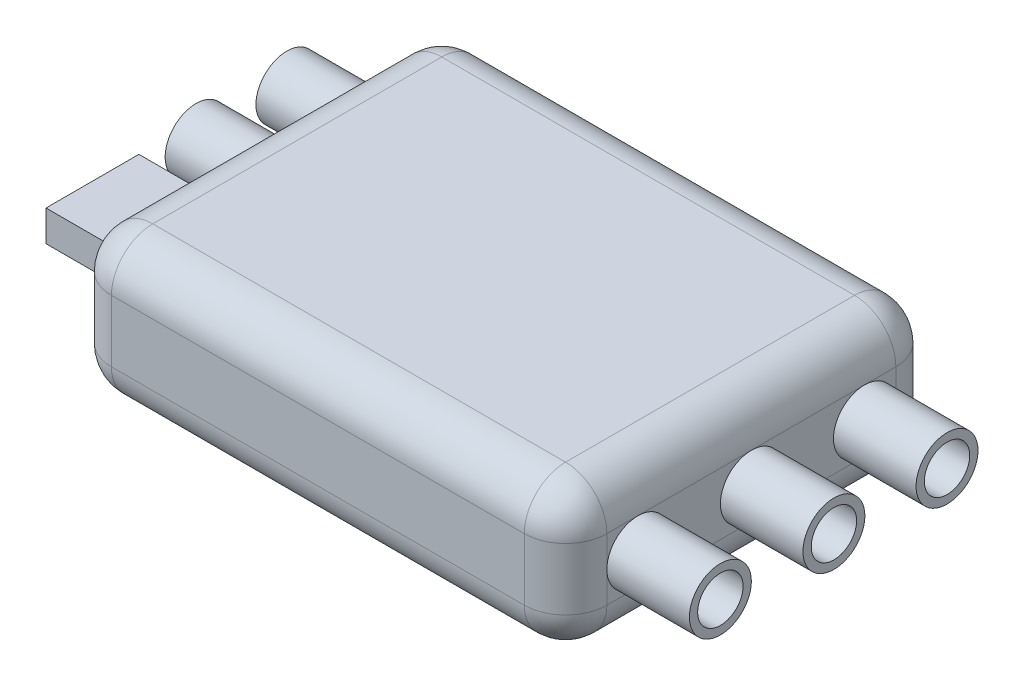
SolidWorks part; units mm, degrees
ref_plane "Front Plane" through (0, 0, 0) normal (0, 0, 1) x (1, 0, 0)
ref_plane "Top Plane" through (0, 0, 0) normal (0, 1, 0) x (1, 0, 0)
ref_plane "Right Plane" through (0, 0, 0) normal (1, 0, 0) x (0, 0, -1)
sketch "Sketch1" plane through (0, 0, 0) normal (0, 1, 0) x (1, 0, 0)
  line L1 (-10, 9) -> (10, 9)
  line L2 (-12, 7) -> (-12, -7)
  line L3 (-10, -9) -> (10, -9)
  line L4 (12, 7) -> (12, -7)
  line L5 (-12, 9) -> (12, -9) construction
  line L6 (-12, -9) -> (12, 9) construction
  arc A0 (-12, -7) -> (-10, -9) centre (-10, -7) ccw
  arc A1 (10, -9) -> (12, -7) centre (10, -7) ccw
  arc A2 (10, 9) -> (12, 7) centre (10, 7) cw
  arc A3 (-10, 9) -> (-12, 7) centre (-10, 7) ccw
  point P0 (0, 0)
  dimension "D3" = 2
  dimension "D1" = 24
  dimension "D2" = 18
extrude "Boss-Extrude1" add sketch "Sketch1" along normal blind 7
fillet "Fillet1" radius 2 16 edges at (0, 0, 9) (11.4142, 0, 8.4142) (12, 0, 0) (11.4142, 0, -8.4142) (0, 0, -9) (-11.4142, 0, -8.4142) (-12, 0, 0) (-11.4142, 0, 8.4142) (-12, 7, 0) (-11.4142, 7, -8.4142) (0, 7, -9) (11.4142, 7, -8.4142) (12, 7, 0) (11.4142, 7, 8.4142) (0, 7, 9) (-11.4142, 7, 8.4142)
sketch "Sketch2" plane through (12, 0, 0) normal (1, 0, 0) x (0, 0, -1)
  line L0 (-7, 3.5) -> (7, 3.5) construction
  line L1 (-7, 5) -> (-7, 2) construction
  line L2 (7, 5) -> (7, 2) construction
  circle A0 centre (0, 3.5) radius 1.5
  circle A1 centre (0, 3.5) radius 1.1
  circle A2 centre (-5.5, 3.5) radius 1.5
  circle A3 centre (-5.5, 3.5) radius 1.1
  circle A4 centre (5.48, 3.5) radius 1.5
  circle A5 centre (5.48, 3.5) radius 1.1
  dimension "D1" = 3
  dimension "D2" = 0.4
extrude "Boss-Extrude2" add sketch "Sketch2" along normal blind 4
sketch "Sketch3" plane through (-12, 0, 0) normal (-1, 0, 0) x (0, 0, 1)
  line L0 (-7, 3.5) -> (7, 3.5) construction
  line L1 (-7, 5) -> (-7, 2) construction
  line L2 (7, 5) -> (7, 2) construction
  line L4 (1.671, 4.25) -> (6.171, 4.25)
  line L5 (1.671, 4.25) -> (1.671, 2.75)
  line L6 (1.671, 2.75) -> (6.171, 2.75)
  line L7 (6.171, 4.25) -> (6.171, 2.75)
  line L8 (1.671, 4.25) -> (6.171, 2.75) construction
  line L9 (1.671, 2.75) -> (6.171, 4.25) construction
  circle A0 centre (-5.5, 3.5) radius 1.5
  circle A1 centre (-1.1, 3.5) radius 1.5
  circle A2 centre (-5.5, 3.5) radius 1.1
  circle A3 centre (-1.1, 3.5) radius 1.1
  point P6 (3.921, 3.5)
  point P11 (3.921, 4.25)
  dimension "D3" = 3
  dimension "D4" = 0.4
  dimension "D5" = 0.4
  dimension "D1" = 4.5
  dimension "D2" = 1.5
  dimension "D6" = 4.4
extrude "Boss-Extrude3" add sketch "Sketch3" along normal blind 4
